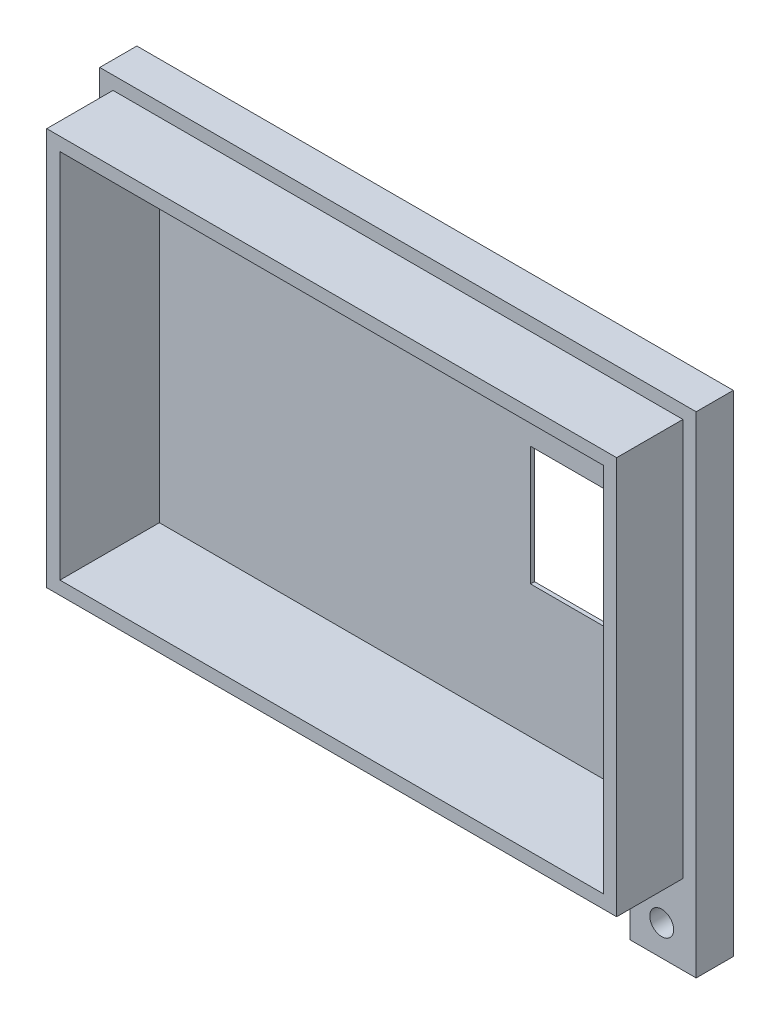
SolidWorks part; units mm, degrees
ref_plane "Plan de face" through (0, 0, 0) normal (0, 0, 1) x (1, 0, 0)
ref_plane "Plan de dessus" through (0, 0, 0) normal (0, 1, 0) x (1, 0, 0)
ref_plane "Plan de droite" through (0, 0, 0) normal (1, 0, 0) x (0, 0, -1)
sketch "Esquisse1" plane through (0, 0, 0) normal (0, 0, 1) x (1, 0, 0)
  line L1 (-15.0756, 11.9167) -> (29.9244, 11.9167)
  line L2 (-15.0756, 11.9167) -> (-15.0756, -20.0833)
  line L3 (-15.0756, -20.0833) -> (29.9244, -20.0833)
  line L4 (29.9244, 11.9167) -> (29.9244, -20.0833)
  dimension "D1" = 45
  dimension "D2" = 32
extrude "Boss.-Extru.1" add sketch "Esquisse1" along normal blind 7.8
sketch "Esquisse2" plane through (0, 0, 7.8) normal (0, 0, 1) x (1, 0, 0)
  line L20 (-13.0756, 9.9167) -> (-13.0756, -18.0833)
  line L21 (-13.0756, -18.0833) -> (27.9244, -18.0833)
  line L22 (27.9244, -18.0833) -> (27.9244, 9.9167)
  line L23 (27.9244, 9.9167) -> (-13.0756, 9.9167)
  line L24 (-13.0756, 9.9167) -> (-13.0756, -18.0833)
  line L25 (-13.0756, -18.0833) -> (27.9244, -18.0833)
  line L26 (27.9244, -18.0833) -> (27.9244, 9.9167)
  line L27 (27.9244, 9.9167) -> (-13.0756, 9.9167)
  dimension "D1" = 2
extrude "Enlèv. mat.-Extru.1" cut sketch "Esquisse2" against normal blind 7.5
sketch "Esquisse4" plane through (0, 0, 7.8) normal (0, 0, 1) x (1, 0, 0)
  line L8 (-14.0756, 10.9167) -> (-14.0756, -19.0833)
  line L9 (-14.0756, -19.0833) -> (28.9244, -19.0833)
  line L10 (28.9244, -19.0833) -> (28.9244, 10.9167)
  line L11 (28.9244, 10.9167) -> (-14.0756, 10.9167)
  line L12 (-14.0756, 10.9167) -> (-14.0756, -19.0833)
  line L13 (-14.0756, -19.0833) -> (28.9244, -19.0833)
  line L14 (28.9244, -19.0833) -> (28.9244, 10.9167)
  line L15 (28.9244, 10.9167) -> (-14.0756, 10.9167)
  dimension "D1" = 1
extrude "Enlèv. mat.-Extru.2" cut sketch "Esquisse4" against normal blind 5 flip side to cut
sketch "Esquisse5" plane through (0, 0, 0) normal (0, 0, -1) x (-1, 0, 0)
  line L0 (-29.9244, 11.9167) -> (15.0756, 11.9167) construction
  line L1 (-23.9244, 0.9167) -> (-14.9244, 0.9167)
  line L2 (-23.9244, 0.9167) -> (-23.9244, -8.0833)
  line L3 (-23.9244, -8.0833) -> (-14.9244, -8.0833)
  line L4 (-14.9244, 0.9167) -> (-14.9244, -8.0833)
  line L5 (15.0756, -20.0833) -> (-29.9244, -20.0833) construction
  line L6 (-29.9244, -20.0833) -> (-29.9244, 11.9167) construction
  dimension "D1" = 9
  dimension "D2" = 9
  dimension "D3" = 11
  dimension "D4" = 12
  dimension "D5" = 6
extrude "Enlèv. mat.-Extru.3" cut sketch "Esquisse5" against normal blind 5
sketch "Esquisse6" plane through (0, 0, 0) normal (0, 0, -1) x (-1, 0, 0)
  line L1 (-29.9244, -20.0833) -> (-24.9244, -20.0833)
  line L2 (-29.9244, -20.0833) -> (-29.9244, -25.0833)
  line L3 (-29.9244, -25.0833) -> (-24.9244, -25.0833)
  line L4 (-24.9244, -20.0833) -> (-24.9244, -25.0833)
  dimension "D1" = 5
  dimension "D2" = 5
extrude "Boss.-Extru.2" add sketch "Esquisse6" against normal up to surface (2.8 mm away) up to face at (7.4244, -4.0833, 2.8)
hole_wizard "Chambrage pour vis à tête ronde bombée M1.61" positions "Esquisse8" profile "Esquisse7" counterbore size "M1.6" standard "ISO"
sketch "Esquisse8" plane through (0, 0, 0) normal (0, 0, -1) x (-1, 0, 0)
  line L0 (-29.9244, -25.0833) -> (-24.9244, -25.0833) construction
  line L1 (-29.9244, -25.0833) -> (-29.9244, 11.9167) construction
  point P0 (-27.325, -22.7833)
  point P1 (-27.325, -22.7833)
  dimension "D1" = 2.3
  dimension "D2" = 2.5994
sketch "Esquisse7" plane through (27.325, -22.7833, 0) normal (1, 0, 0) x (0, 1, 0)
  line L0 (0, 0) -> (0, 7.7908)
  line L1 (0, 7.7908) -> (0.9, 7.25)
  line L2 (0.9, 7.25) -> (0.9, 1.3)
  line L3 (0.9, 1.3) -> (1.75, 1.3)
  line L5 (1.75, 1.3) -> (1.75, 0.025)
  line L6 (1.75, 0.025) -> (1.775, 0)
  line L7 (1.775, 0) -> (0, 0)
  line L8 (-1.75, 0.025) -> (-1.775, 0) construction
  line L10 (0, 7.7908) -> (-0.9, 7.25) construction
  line L11 (0, -6.35) -> (0, 107.95) construction
  dimension "Diamètre du perçage" = 1.8
  dimension "Profondeur du perçage" = 7.25
  dimension "Diamètre du chambrage" = 3.5
  dimension "Profondeur du chambrage" = 1.3
  dimension "Diamètre du fraisage entrant" = 3.55
  dimension "Angle du fraisage entrant" = 90
  dimension "Angle de pointe" = 118
ref_plane "Plan1" through (0, 0, -0.5) normal (0, 0, -1) x (-1, 0, 0)
